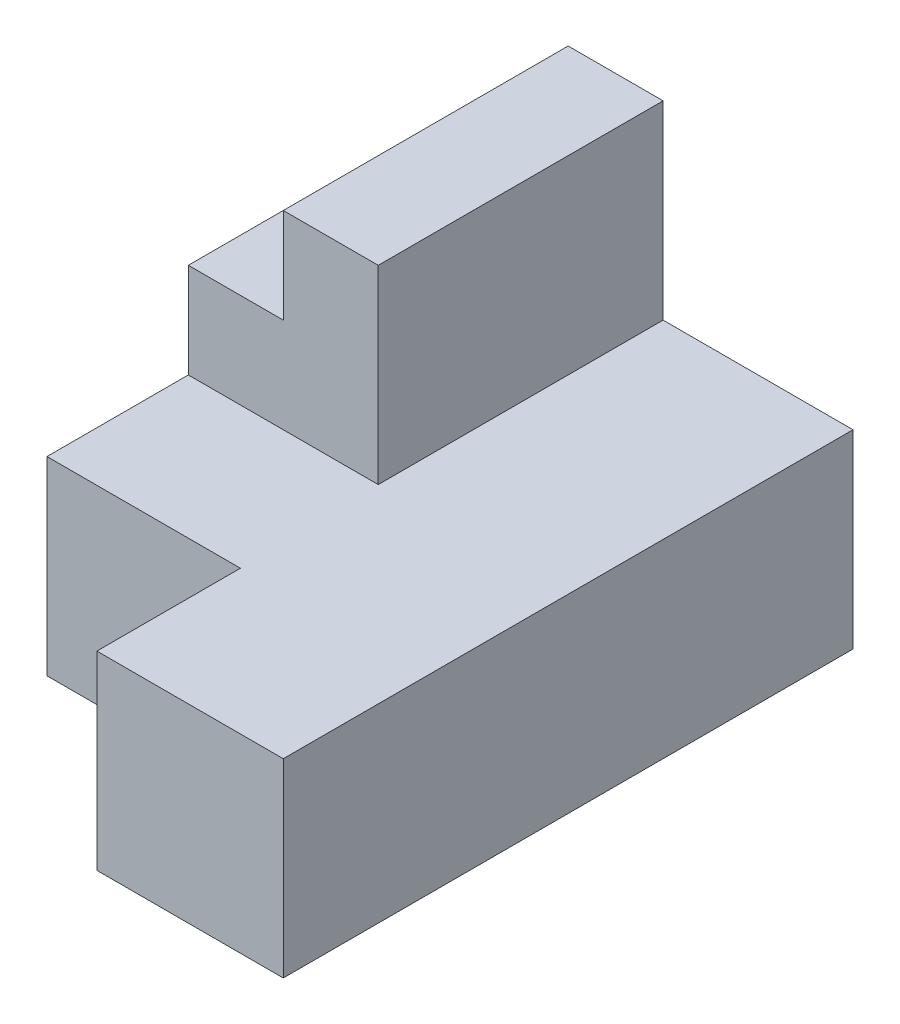
SolidWorks part; units mm, degrees
ref_plane "Front Plane" through (0, 0, 0) normal (0, 0, 1) x (1, 0, 0)
ref_plane "Top Plane" through (0, 0, 0) normal (0, 1, 0) x (1, 0, 0)
ref_plane "Right Plane" through (0, 0, 0) normal (1, 0, 0) x (0, 0, -1)
sketch "Sketch1" plane through (0, 0, 0) normal (0, 0, 1) x (1, 0, 0)
  line L1 (0, 0) -> (40, 0)
  line L2 (0, 0) -> (0, 40)
  line L3 (0, 40) -> (40, 40)
  line L4 (40, 0) -> (40, 40)
extrude "Boss-Extrude1" add sketch "Sketch1" along normal blind 60
sketch "Sketch2" plane through (0, 40, 0) normal (0, 1, 0) x (1, 0, 0)
  line L0 (40, -60) -> (0, -60) construction
  line L1 (40, 0) -> (20, 0)
  line L2 (40, 0) -> (40, -60)
  line L3 (40, -60) -> (20, -60)
  line L4 (20, 0) -> (20, -60)
extrude "Cut-Extrude1" cut sketch "Sketch2" against normal blind 20
sketch "Sketch3" plane through (0, 40, 0) normal (0, 1, 0) x (1, 0, 0)
  line L0 (0, -60) -> (0, 0) construction
  line L1 (10, 0) -> (0, 0)
  line L3 (10, -30) -> (0, -30)
  line L4 (0, 0) -> (0, -30)
  line L9 (10, 0) -> (10, -30)
extrude "Cut-Extrude2" cut sketch "Sketch3" against normal blind 10
sketch "Sketch4" plane through (0, 40, 0) normal (0, 1, 0) x (1, 0, 0)
  line L0 (20, 0) -> (20, -60) construction
  line L1 (0, -60) -> (20, -60)
  line L2 (0, -60) -> (0, -30)
  line L3 (0, -30) -> (20, -30)
  line L4 (20, -60) -> (20, -30)
extrude "Cut-Extrude3" cut sketch "Sketch4" against normal blind 20
sketch "Sketch5" plane through (0, 20, 0) normal (0, 1, 0) x (1, 0, 0)
  line L1 (0, -60) -> (20.369, -60)
  line L2 (0, -60) -> (0, -44.8834)
  line L3 (0, -44.8834) -> (20.369, -44.8834)
  line L4 (20.369, -60) -> (20.369, -44.8834)
extrude "Cut-Extrude4" cut sketch "Sketch5" against normal blind 20
